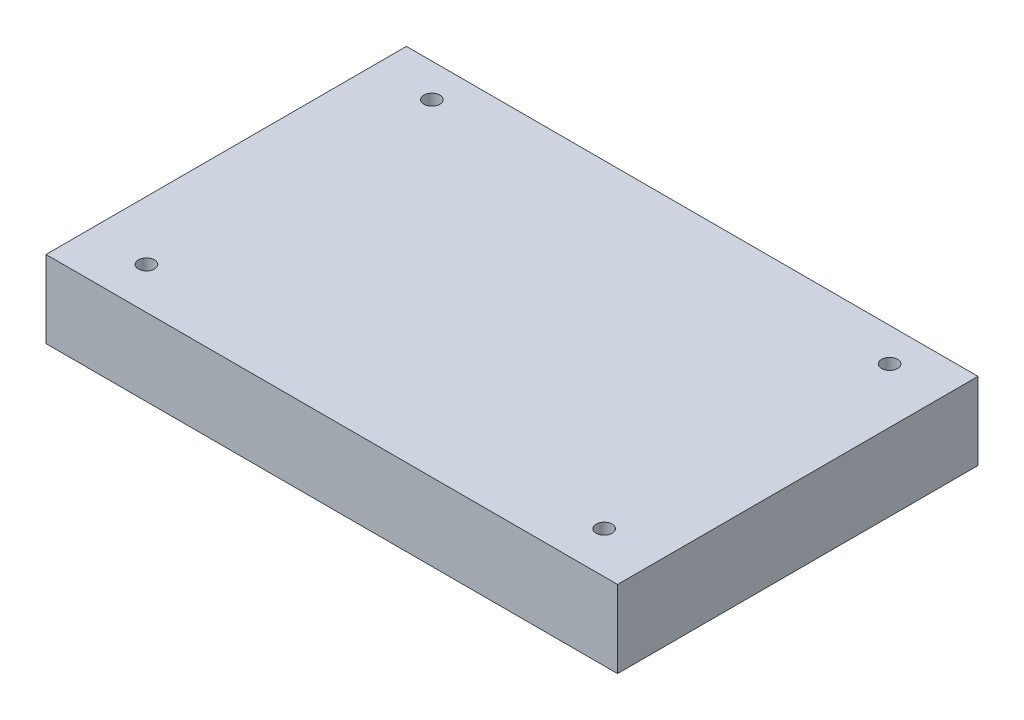
SolidWorks part; units mm, degrees
ref_plane "Front Plane" through (0, 0, 0) normal (0, 0, 1) x (1, 0, 0)
ref_plane "Top Plane" through (0, 0, 0) normal (0, 1, 0) x (1, 0, 0)
ref_plane "Right Plane" through (0, 0, 0) normal (1, 0, 0) x (0, 0, -1)
sketch "Sketch1" plane through (0, 0, 0) normal (0, 1, 0) x (1, 0, 0)
  line L1 (-55.5, 35) -> (55.5, 35)
  line L2 (-55.5, 35) -> (-55.5, -35)
  line L3 (-55.5, -35) -> (55.5, -35)
  line L4 (55.5, 35) -> (55.5, -35)
  line L5 (-55.5, 35) -> (55.5, -35) construction
  line L6 (-55.5, -35) -> (55.5, 35) construction
  point P0 (0, 0)
  dimension "D1" = 70
  dimension "D2" = 111
extrude "Boss-Extrude1" add sketch "Sketch1" along normal blind 15
sketch "Sketch2" plane through (0, 15, 0) normal (0, 1, 0) x (1, 0, 0)
  line L0 (44.825, -28.48) -> (44.825, -35) construction
  line L1 (-44.065, 28.505) -> (44.825, 28.505) construction
  line L2 (-44.065, 28.505) -> (-44.065, -26.925) construction
  line L3 (-44.065, -26.925) -> (44.825, -26.925) construction
  line L4 (44.825, 28.505) -> (44.825, -26.925) construction
  line L5 (-55.5, -35) -> (55.5, -35) construction
  line L6 (46.38, -26.925) -> (55.5, -26.925) construction
  line L7 (55.5, -35) -> (55.5, 35) construction
  circle A0 centre (-44.065, 28.505) radius 1.555
  circle A1 centre (-44.065, -26.925) radius 1.555
  circle A2 centre (44.825, -26.925) radius 1.555
  circle A3 centre (44.825, 28.505) radius 1.555
  dimension "D1" = 3.11
  dimension "D2" = 55.43
  dimension "D3" = 88.89
  dimension "D4" = 6.52
  dimension "D5" = 9.12
extrude "Cut-Extrude1" cut sketch "Sketch2" against normal blind 15
